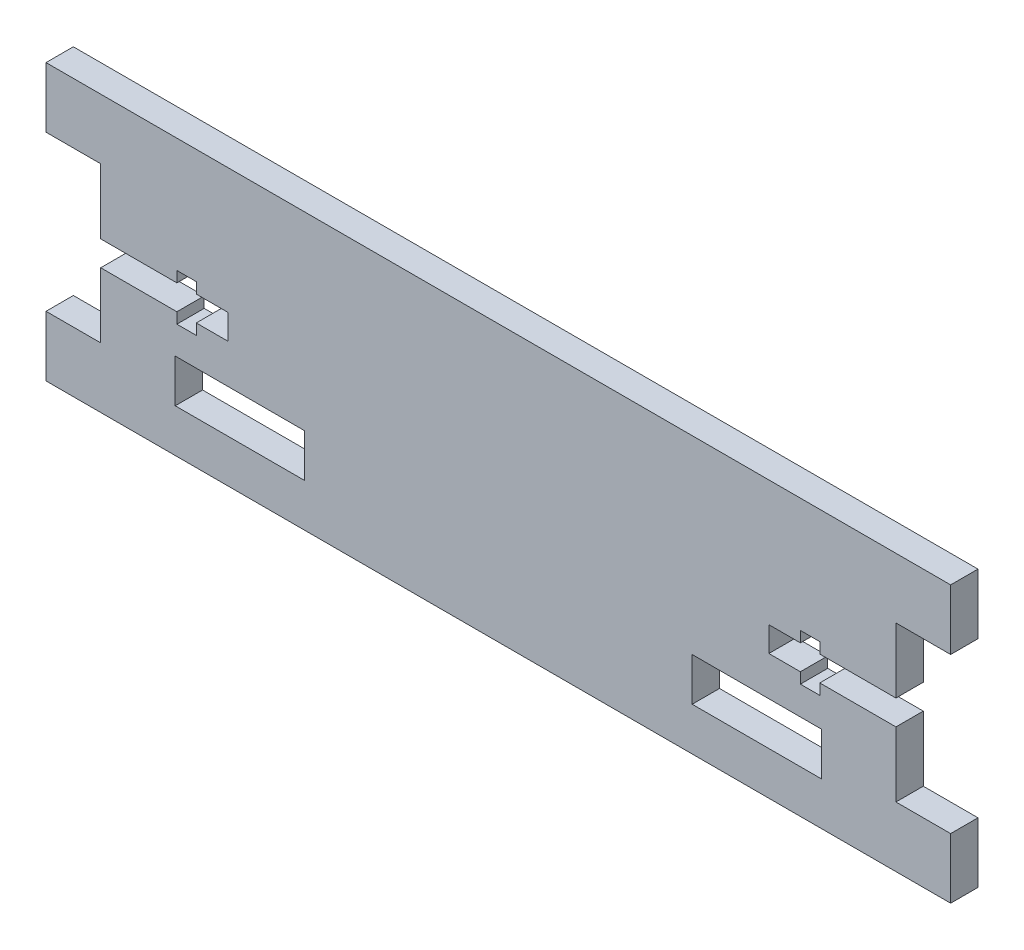
SolidWorks part; units mm, degrees
ref_plane "Front Plane" through (0, 0, 0) normal (0, 0, 1) x (1, 0, 0)
ref_plane "Top Plane" through (0, 0, 0) normal (0, 1, 0) x (1, 0, 0)
ref_plane "Right Plane" through (0, 0, 0) normal (1, 0, 0) x (0, 0, -1)
sketch "Sketch1" plane through (0, 0, 0) normal (0, 0, 1) x (1, 0, 0)
  line L0 (92.1271, 5.9908) -> (92.1271, 12.9908)
  line L1 (-12.8729, 37.9908) -> (92.1271, 37.9908)
  line L2 (92.1271, 37.9908) -> (92.1271, 30.9908)
  line L3 (-12.8729, 5.9908) -> (92.1271, 5.9908)
  line L4 (-12.8729, 37.9908) -> (-12.8729, 30.9908)
  line L5 (2.1271, 15.9908) -> (17.1271, 15.9908)
  line L6 (2.1271, 15.9908) -> (2.1271, 10.9908)
  line L7 (2.1271, 10.9908) -> (17.1271, 10.9908)
  line L8 (17.1271, 15.9908) -> (17.1271, 10.9908)
  line L9 (85.7771, 30.9908) -> (92.1271, 30.9908)
  line L10 (85.7771, 30.9908) -> (85.7771, 23.4408)
  line L11 (85.7771, 12.9908) -> (92.1271, 12.9908)
  line L12 (85.7771, 12.9908) -> (85.7771, 20.5408)
  line L13 (71.0271, 23.4408) -> (74.6871, 23.4408)
  line L14 (71.0271, 23.4408) -> (71.0271, 20.5408)
  line L15 (71.0271, 20.5408) -> (74.6871, 20.5408)
  line L16 (76.9371, 23.4408) -> (85.7771, 23.4408)
  line L17 (74.6871, 24.6908) -> (76.9371, 24.6908)
  line L18 (74.6871, 24.6908) -> (74.6871, 23.4408)
  line L19 (74.6871, 19.2908) -> (76.9371, 19.2908)
  line L20 (76.9371, 24.6908) -> (76.9371, 23.4408)
  line L21 (76.9371, 20.5408) -> (85.7771, 20.5408)
  line L22 (76.9371, 19.2908) -> (76.9371, 20.5408)
  line L23 (74.6871, 19.2908) -> (74.6871, 20.5408)
  line L24 (39.6271, 37.9908) -> (39.6271, 5.9908) construction
  line L25 (4.5671, 19.2908) -> (4.5671, 20.5408)
  line L26 (2.3171, 19.2908) -> (2.3171, 20.5408)
  line L27 (-6.5229, 20.5408) -> (2.3171, 20.5408)
  line L28 (2.3171, 24.6908) -> (2.3171, 23.4408)
  line L29 (2.3171, 19.2908) -> (4.5671, 19.2908)
  line L30 (4.5671, 24.6908) -> (4.5671, 23.4408)
  line L31 (2.3171, 24.6908) -> (4.5671, 24.6908)
  line L32 (-6.5229, 23.4408) -> (2.3171, 23.4408)
  line L33 (4.5671, 20.5408) -> (8.2271, 20.5408)
  line L34 (8.2271, 23.4408) -> (8.2271, 20.5408)
  line L35 (4.5671, 23.4408) -> (8.2271, 23.4408)
  line L36 (-6.5229, 12.9908) -> (-6.5229, 20.5408)
  line L37 (-12.8729, 12.9908) -> (-6.5229, 12.9908)
  line L38 (-6.5229, 30.9908) -> (-6.5229, 23.4408)
  line L39 (-12.8729, 30.9908) -> (-6.5229, 30.9908)
  line L40 (62.1271, 15.9908) -> (62.1271, 10.9908)
  line L41 (-12.8729, 5.9908) -> (-12.8729, 12.9908)
  line L42 (77.1271, 10.9908) -> (62.1271, 10.9908)
  line L43 (77.1271, 15.9908) -> (77.1271, 10.9908)
  line L44 (77.1271, 15.9908) -> (62.1271, 15.9908)
  dimension "D1" = 5
  dimension "D2" = 5
  dimension "D3" = 2.9
  dimension "D4" = 2.25
  dimension "D5" = 8.84
  dimension "D6" = 1.25
  dimension "D7" = 1.25
  dimension "D8" = 3.66
  dimension "D9" = 6.35
  dimension "D10" = 15
  dimension "D11" = 7
  dimension "D12" = 105
  dimension "D13" = 105
  dimension "D14" = 7
  dimension "D15" = 32
  dimension "D16" = 14.55
  dimension "D17" = 15
extrude "Extrude1" add sketch "Sketch1" along normal blind 3.175
